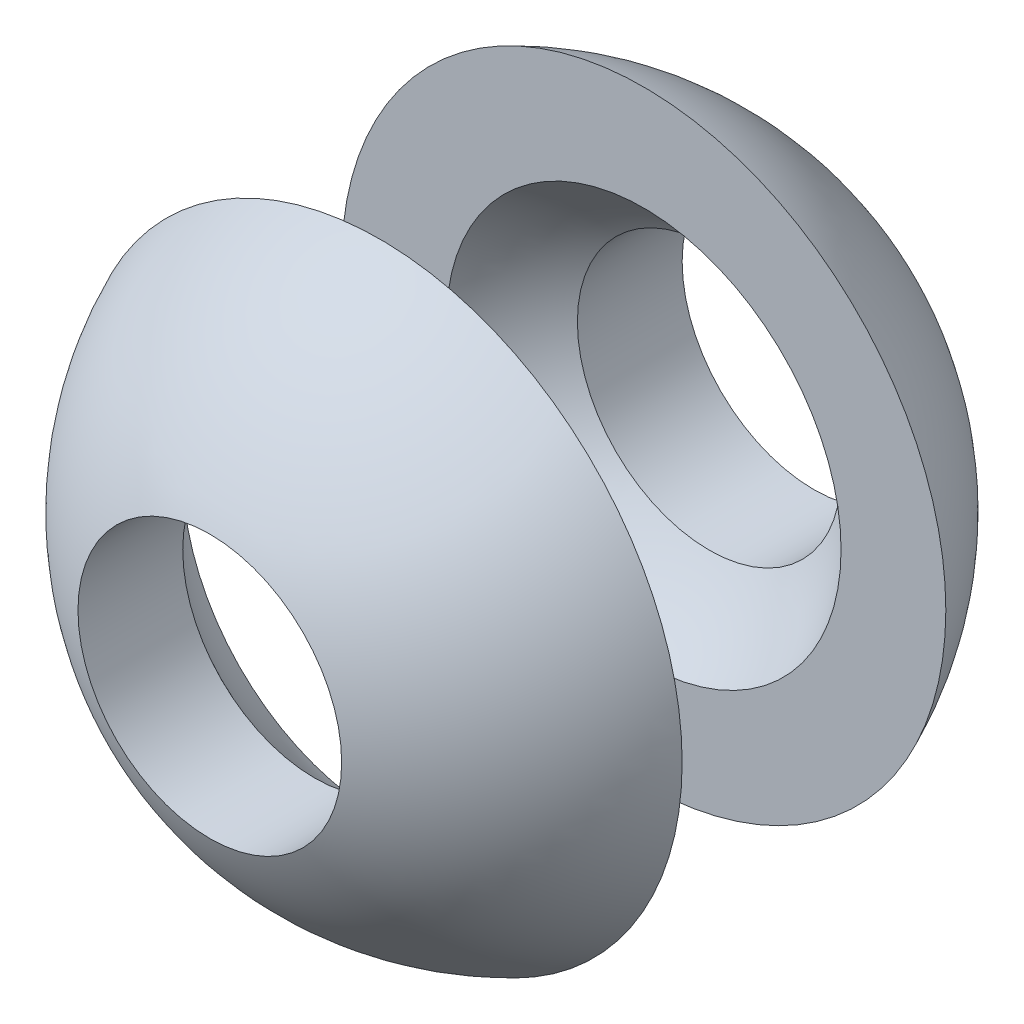
SolidWorks part; units mm, degrees
ref_plane "Front Plane" through (0, 0, 0) normal (0, 0, 1) x (1, 0, 0)
ref_plane "Top Plane" through (0, 0, 0) normal (0, 1, 0) x (1, 0, 0)
ref_plane "Right Plane" through (0, 0, 0) normal (1, 0, 0) x (0, 0, -1)
sketch "Sketch1" plane through (0, 0, 0) normal (0, 1, 0) x (1, 0, 0)
  line L0 (0, 14.5152) -> (0, -14.8657) construction
  line L1 (0, 12.5) -> (0, 9)
  line L2 (0, -9) -> (0, -12.5)
  line L3 (5, 11.4564) -> (5, 7.4833)
  line L5 (7.4833, -5) -> (11.4564, -5)
  line L6 (7.4833, 5) -> (11.4564, 5)
  line L10 (5, -7.4833) -> (5, -11.4564)
  arc A0 (5, -11.4564) -> (11.4564, -5) centre (0, 0) ccw
  arc A1 (5, -7.4833) -> (7.4833, -5) centre (0, 0) ccw
  arc A2 (7.4833, 5) -> (5, 7.4833) centre (0, 0) ccw
  arc A3 (11.4564, 5) -> (5, 11.4564) centre (0, 0) ccw
  dimension "D1" = 25
  dimension "D2" = 18
  dimension "D3" = 5
revolve "Revolve1" add sketch "Sketch1" angle 360 about L0
